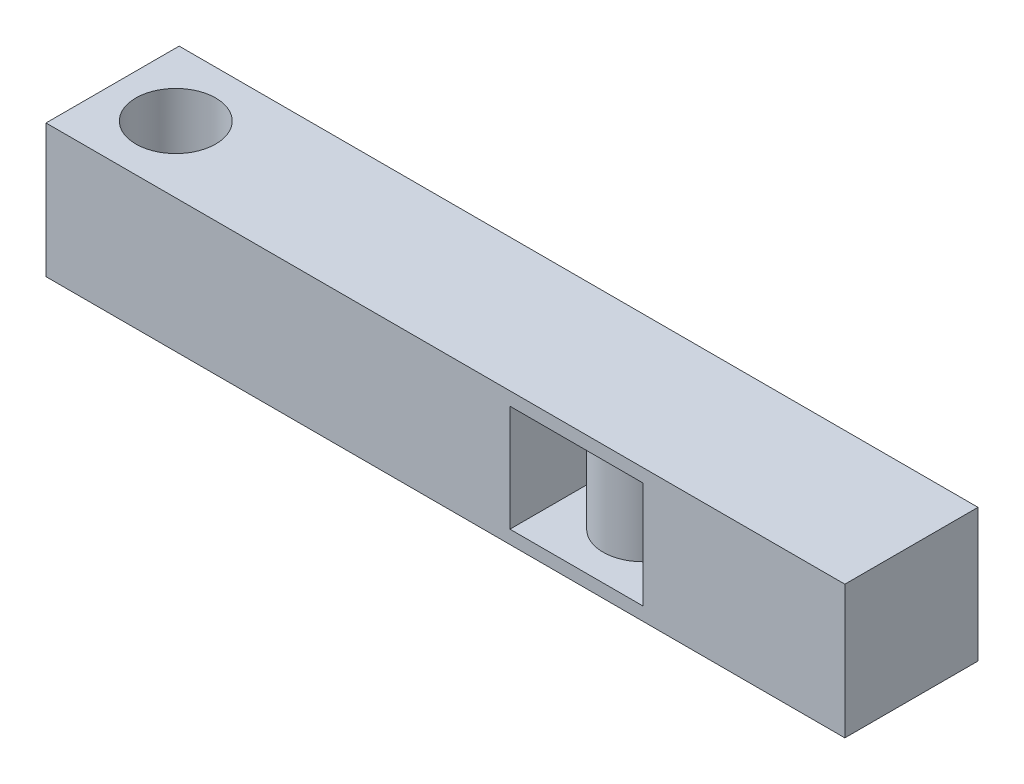
SolidWorks part; units mm, degrees
ref_plane "Front Plane" through (0, 0, 0) normal (0, 0, 1) x (1, 0, 0)
ref_plane "Top Plane" through (0, 0, 0) normal (0, 1, 0) x (1, 0, 0)
ref_plane "Right Plane" through (0, 0, 0) normal (1, 0, 0) x (0, 0, -1)
sketch "Sketch1" plane through (0, 0, 0) normal (0, 0, 1) x (1, 0, 0)
  line L1 (-150, 25) -> (150, 25)
  line L2 (-150, 25) -> (-150, -25)
  line L3 (-150, -25) -> (150, -25)
  line L4 (150, 25) -> (150, -25)
  line L5 (-150, 25) -> (150, -25) construction
  line L6 (-150, -25) -> (150, 25) construction
  point P0 (0, 0)
  dimension "D1" = 50
  dimension "D2" = 300
extrude "Boss-Extrude1" add sketch "Sketch1" along normal blind 50
sketch "Sketch2" plane through (0, 25, 0) normal (0, 1, 0) x (1, 0, 0)
  line L0 (-126.2661, 0) -> (-126.2661, -50) construction
  line L1 (150, 0) -> (-150, 0) construction
  line L2 (150, -50) -> (-150, -50) construction
  circle A0 centre (-126.2661, -25) radius 15
  dimension "D1" = 30
extrude "Cut-Extrude1" cut sketch "Sketch2" against normal through all both and the other way through all
sketch "Sketch3" plane through (0, 25, 0) normal (0, 1, 0) x (1, 0, 0)
  line L0 (-126.2661, -25) -> (49.2339, -25) construction
  line L1 (150, -50) -> (-150, -50) construction
  line L2 (24.2339, 0) -> (74.2339, 0)
  line L3 (24.2339, 0) -> (24.2339, -50)
  line L4 (24.2339, -50) -> (74.2339, -50)
  line L5 (74.2339, 0) -> (74.2339, -50)
  line L6 (24.2339, 0) -> (74.2339, -50) construction
  line L7 (24.2339, -50) -> (74.2339, 0) construction
  dimension "D1" = 175.5
  dimension "D2" = 50
extrude "Cut-Extrude2" cut sketch "Sketch3" against normal blind 40 from offset 5 offset against normal yes
sketch "Sketch4" plane through (0, -20, 0) normal (0, 1, 0) x (1, 0, 0)
  line L0 (24.2339, 0) -> (74.2339, 0) construction
  line L1 (150, 0) -> (-150, 0) construction
  line L2 (49.2339, 0) -> (49.2339, -50) construction
  line L3 (150, -50) -> (-150, -50) construction
  circle A0 centre (49.2339, -25) radius 15
  dimension "D2" = 30
  dimension "D1" = 50
extrude "Boss-Extrude2" add sketch "Sketch4" along normal up to next
sketch "Sketch5" plane through (150, 0, 0) normal (1, 0, 0) x (0, 0, -1)
  line L0 (-50, -25) -> (-50, 25) construction
  line L1 (-50, 25) -> (0, 25) construction
